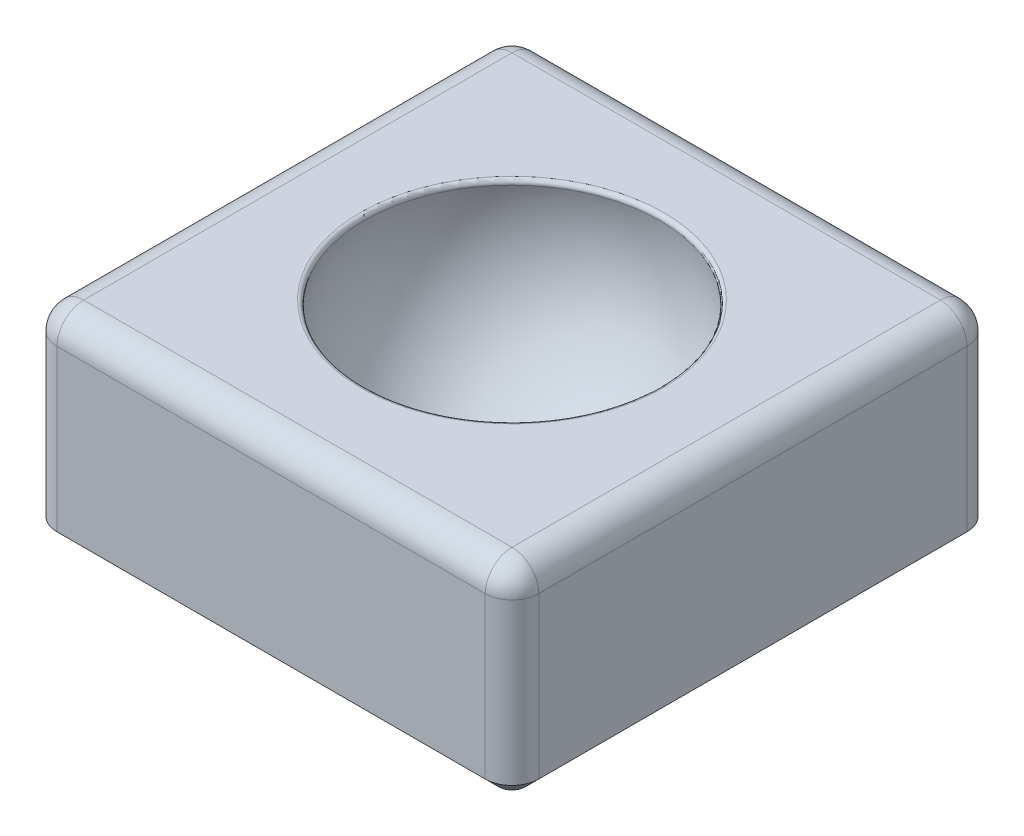
SolidWorks part; units mm, degrees
ref_plane "Спереди" through (0, 0, 0) normal (0, 0, 1) x (1, 0, 0)
ref_plane "Сверху" through (0, 0, 0) normal (0, 1, 0) x (1, 0, 0)
ref_plane "Справа" through (0, 0, 0) normal (1, 0, 0) x (0, 0, -1)
sketch "Эскиз1" plane through (0, 0, 0) normal (0, 1, 0) x (1, 0, 0)
  line L1 (-18, -18) -> (18, -18)
  line L2 (-18, -18) -> (-18, 18)
  line L3 (-18, 18) -> (18, 18)
  line L4 (18, -18) -> (18, 18)
  line L5 (0, 18) -> (0, -18) construction
  line L6 (-18, 0) -> (18, 0) construction
  point P0 (0, 0)
  dimension "D1" = 36
  dimension "D2" = 36
extrude "Бобышка-Вытянуть1" add sketch "Эскиз1" along normal blind 15
ref_plane "Плоскость4" through (0, 12, 0) normal (0, 1, 0) x (1, 0, 0)
sketch "Эскиз4" plane through (0, 12, 0) normal (0, 1, 0) x (1, 0, 0)
  line L0 (-23.5139, 0) -> (32.0068, 0) construction
  line L1 (-11.35, 0) -> (11.35, 0)
  arc A0 (-11.35, 0) -> (11.35, 0) centre (0, 0) cw
  point P5 (0, 0)
  dimension "D1" = 22.7
revolve "Вырез-Повернуть2" cut sketch "Эскиз4" angle 360 about L0
fillet "Скругление1" radius 0.3 1 edges at (0, 15, -10.9463)
fillet "Скругление2" radius 2 8 edges at (0, 15, -18) (18, 15, 0) (0, 15, 18) (-18, 15, 0) (-18, 7.5, -18) (-18, 7.5, 18) (18, 7.5, -18) (18, 7.5, 18)
sketch "Эскиз5" plane through (0, 0, 0) normal (0, -1, 0) x (1, 0, 0)
  circle A0 centre (0, 0) radius 3
  dimension "D1" = 6
extrude "Вырез-Вытянуть1" cut sketch "Эскиз5" against normal blind 10
chamfer "Фаска1" distance 1 angle 45 9 edges at (-17.4142, 0, 17.4142) (0, 0, 18) (17.4142, 0, 17.4142) (18, 0, 0) (17.4142, 0, -17.4142) (0, 0, -18) (-17.4142, 0, -17.4142) (-18, 0, 0) (0, 0, -3)
